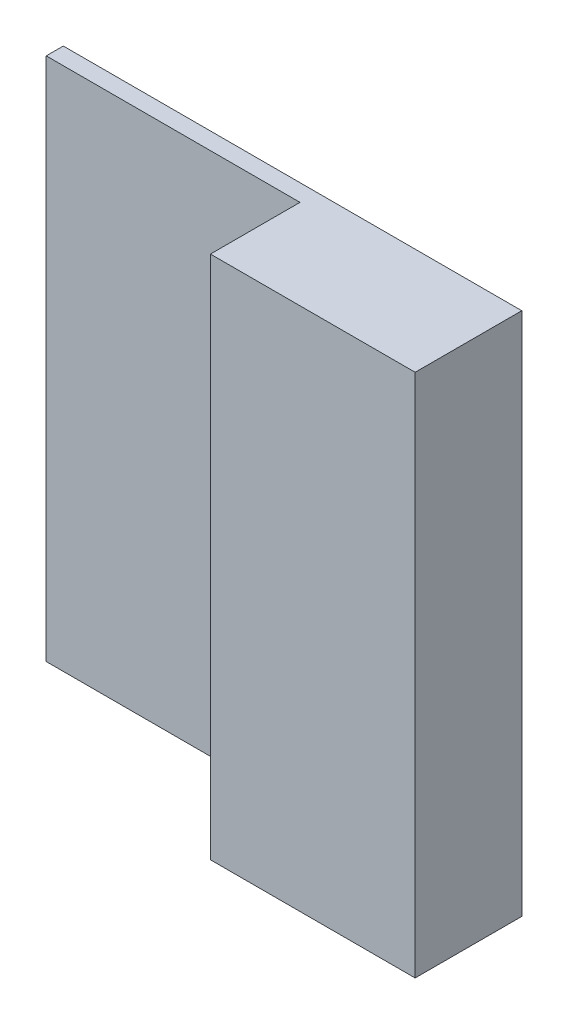
SolidWorks part; units mm, degrees
ref_plane "Front" through (0, 0, 0) normal (0, 0, 1) x (1, 0, 0)
ref_plane "Top" through (0, 0, 0) normal (0, 1, 0) x (1, 0, 0)
ref_plane "Right" through (0, 0, 0) normal (1, 0, 0) x (0, 0, -1)
sketch "Sketch1" plane through (0, 0, 0) normal (0, 1, 0) x (1, 0, 0)
  line L1 (0, 0) -> (-44, 0)
  line L2 (0, 0) -> (0, 4)
  line L3 (0, 4) -> (-44, 4)
  line L4 (-44, 0) -> (-44, 4)
  line L5 (-44, 0) -> (-48, 0)
  line L6 (-44, 0) -> (-44, 25)
  line L7 (-44, 25) -> (-48, 25)
  line L8 (-48, 0) -> (-48, 25)
  line L9 (-44, 25) -> (-107.5, 25)
  line L10 (-44, 25) -> (-44, 21)
  line L11 (-44, 21) -> (-107.5, 21)
  line L12 (-107.5, 25) -> (-107.5, 21)
  line L13 (-44, 25) -> (0, 25)
  line L14 (-44, 25) -> (-44, 4)
  line L15 (-44, 4) -> (0, 4)
  line L16 (0, 25) -> (0, 4)
  dimension "D1" = 4
  dimension "D2" = 44
  dimension "D3" = 4
  dimension "D4" = 25
  dimension "D5" = 4
  dimension "D6" = 63.5
extrude "Boss-Extrude1" add sketch "Sketch1" along normal blind 123 contours L9 L12 L11 L8 | L11 L6 L7 L8 | L6 L11 L8 L5 L4 | L4 L1 L2 L3 | L16 L13 L6 L3
